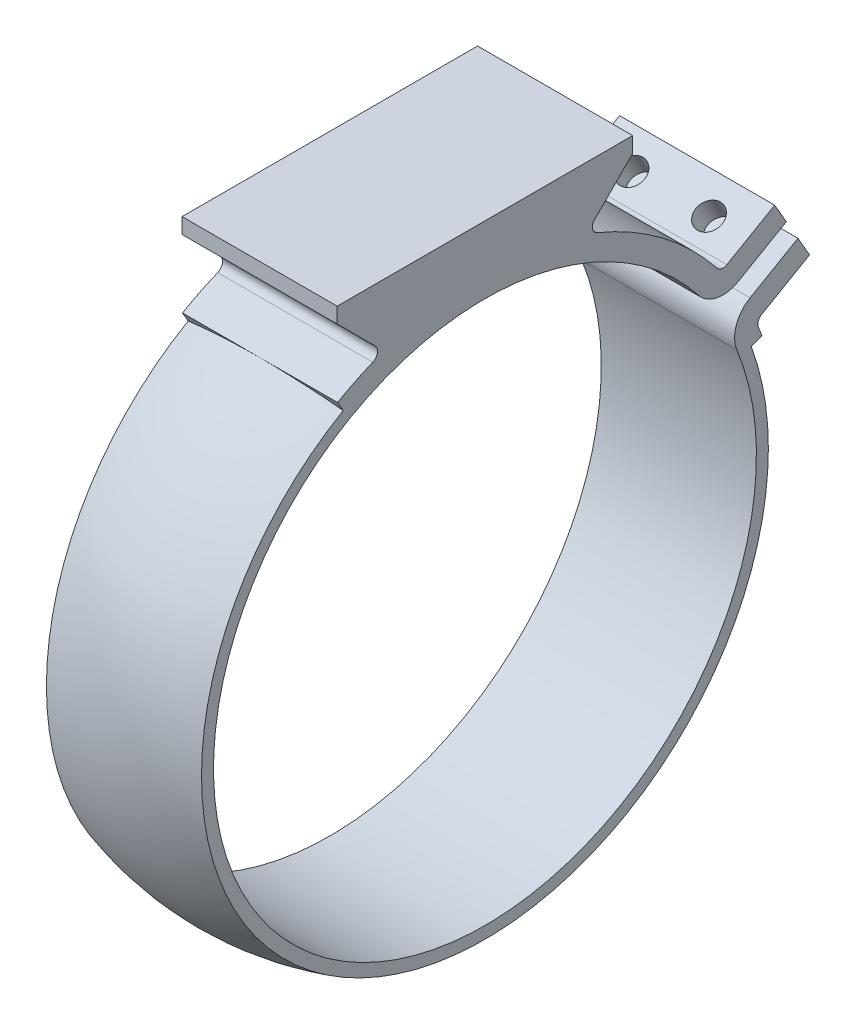
SolidWorks part; units mm, degrees
ref_plane "Front Plane" through (0, 0, 0) normal (0, 0, 1) x (1, 0, 0)
ref_plane "Top Plane" through (0, 0, 0) normal (0, 1, 0) x (1, 0, 0)
ref_plane "Right Plane" through (0, 0, 0) normal (1, 0, 0) x (0, 0, -1)
sketch "Sketch1" plane through (0, 0, 0) normal (1, 0, 0) x (0, 0, -1)
  line L4 (-19.05, 43.6889) -> (19.05, 43.6889)
  line L5 (19.05, 43.6889) -> (19.05, 41.6889)
  line L6 (19.05, 41.6889) -> (13.05, 35.6889)
  line L8 (-13.05, 35.6889) -> (-19.05, 41.6889)
  line L9 (-19.05, 41.6889) -> (-19.05, 43.6889)
  line L10 (29.533, 18.783) -> (38.8556, 24.1653)
  line L11 (38.8556, 24.1653) -> (37.3556, 26.7634)
  line L12 (37.3556, 26.7634) -> (30.4274, 22.7634)
  line L13 (31.033, 16.1849) -> (40.3556, 21.5673)
  line L14 (40.3556, 21.5673) -> (41.8556, 18.9692)
  line L15 (41.8556, 18.9692) -> (34.9274, 14.9692)
  line L16 (0, 0) -> (62.4817, 36.0738) construction
  line L17 (0, 0) -> (0, 16.1849) construction
  arc A0 (29.533, 18.783) -> (31.033, 16.1849) centre (0, 0) ccw
  arc A1 (-13.05, 35.6889) -> (34.9274, 14.9692) centre (0, 0) ccw
  arc A2 (30.4274, 22.7634) -> (13.05, 35.6889) centre (0, 0) ccw
  point P7 (0, 43.6889)
  dimension "D1" = 3
  dimension "D2" = 70
  dimension "D3" = 45
  dimension "D4" = 2
  dimension "D5" = 38.1
  dimension "D6" = 8
  dimension "D7" = 45
  dimension "D8" = 1.5
  dimension "D9" = 1.5
  dimension "D10" = 3
  dimension "D11" = 3
  dimension "D12" = 60
  dimension "D13" = 8
extrude "Boss-Extrude1" add sketch "Sketch1" along normal blind 20
fillet "Fillet1" radius 1 4 edges at (10, 35.6889, 13.05) (10, 35.6889, -13.05) (10, 22.7634, -30.4274) (10, 14.9692, -34.9274)
fillet "Fillet2" radius 4 2 edges at (10, 16.1849, -31.033) (10, 18.783, -29.533)
hole_wizard "CSK for M3 Countersunk Flat Head Screw1" positions "Sketch2" profile "Sketch3" countersink size "M3" standard "DIN"
sketch "Sketch2" plane through (0, -3.8971, -2.25) normal (0, -0.866, -0.5) x (-1, 0, 0)
  line L0 (-20, 45.7326) -> (0, 45.7326) construction
  line L1 (-20, 38.6102) -> (-20, 45.7326) construction
  line L2 (0, 38.6102) -> (0, 45.7326) construction
  point P0 (-15, 41.7326)
  point P2 (-5, 41.7326)
  dimension "D1" = 4
  dimension "D2" = 5
  dimension "D3" = 5
  dimension "D4" = 4
sketch "Sketch3" plane through (15, 16.9692, -38.3915) normal (1, 0, 0) x (0, 0.5, -0.866)
  line L0 (0, 0) -> (0, 61.3357)
  line L1 (0, 61.3357) -> (1.7, 61.3357)
  line L2 (1.7, 61.3357) -> (1.7, 1.45)
  line L3 (1.7, 1.45) -> (3.15, 0)
  line L5 (3.15, 0) -> (0, 0)
  line L6 (-1.7, 1.45) -> (-3.15, 0) construction
  line L11 (0, -6.35) -> (0, 107.95) construction
  dimension "Thru Hole Dia." = 3.4
  dimension "Thru Hole Depth" = 61.3357
  dimension "Near C'Sink Dia." = 6.3
  dimension "Near C'Sink Angle" = 90
sketch "Sketch4" plane through (0, 0, 0) normal (0, 0, 1) x (1, 0, 0)
  line L0 (0, 35.141) -> (0, -38) construction
  line L1 (0, -38) -> (20, -38) construction
  line L2 (20, 43.6889) -> (0, 43.6889) construction
  line L3 (-8.0027, -33.015) -> (-8.0027, -46)
  line L4 (-8.0027, -46) -> (28, -46)
  line L5 (28, -46) -> (28, -33.0167)
  line L6 (20, -38) -> (20, 35.141) construction
  line L7 (-3.5587, 0) -> (66.4998, 0) construction
  arc A1 (-8.0027, -33.015) -> (28, -33.0167) centre (10, -3) ccw
  point P9 (10, 43.6889)
  dimension "D1" = 70
  dimension "D2" = 8.0027
  dimension "D3" = 8
  dimension "D4" = 8
revolve "Cut-Revolve1" cut sketch "Sketch4" angle 110 about L7 other way angle 150
